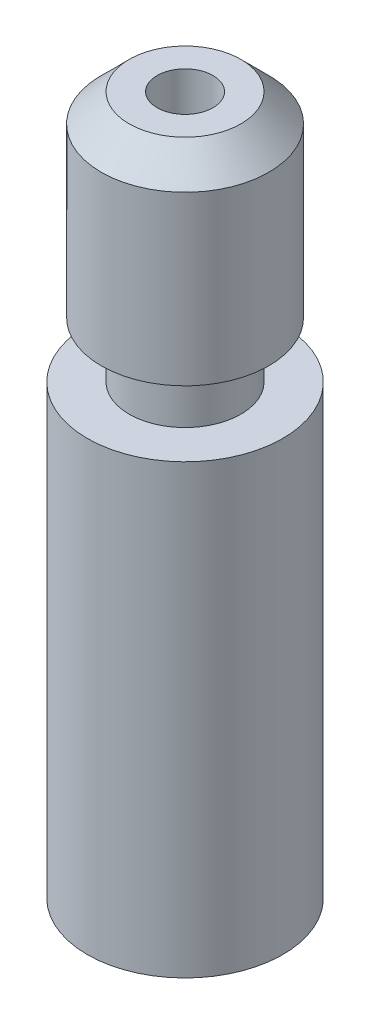
SolidWorks part; units mm, degrees
ref_plane "前基準面" through (0, 0, 0) normal (0, 0, 1) x (1, 0, 0)
ref_plane "上基準面" through (0, 0, 0) normal (0, 1, 0) x (1, 0, 0)
ref_plane "右基準面" through (0, 0, 0) normal (1, 0, 0) x (0, 0, -1)
sketch "草圖1" plane through (0, 0, 0) normal (0, 1, 0) x (1, 0, 0)
  circle A0 centre (0, 0) radius 3.5
  dimension "D1" = 7
extrude "填料-伸長1" add sketch "草圖1" along normal blind 16
sketch "草圖2" plane through (0, 0, 0) normal (0, 1, 0) x (1, 0, 0)
  circle A0 centre (0, 0) radius 2
  dimension "D1" = 4
extrude "填料-伸長2" add sketch "草圖2" along normal blind 25
sketch "草圖3" plane through (0, 25, 0) normal (0, 1, 0) x (1, 0, 0)
  circle A0 centre (0, 0) radius 3
  dimension "D1" = 6
extrude "填料-伸長3" add sketch "草圖3" against normal blind 7
chamfer "導角1" distance 1 angle 45 1 edges at (0, 25, 3)
sketch "草圖4" plane through (0, 25, 0) normal (0, 1, 0) x (1, 0, 0)
  circle A0 centre (0, 0) radius 1
  dimension "D1" = 2
extrude "除料-伸長1" cut sketch "草圖4" against normal through all
sketch "草圖5" plane through (0, 0, 0) normal (0, -1, 0) x (-1, 0, 0)
  circle A0 centre (0, 0) radius 2
  dimension "D1" = 4
extrude "除料-伸長2" cut sketch "草圖5" against normal blind 2
